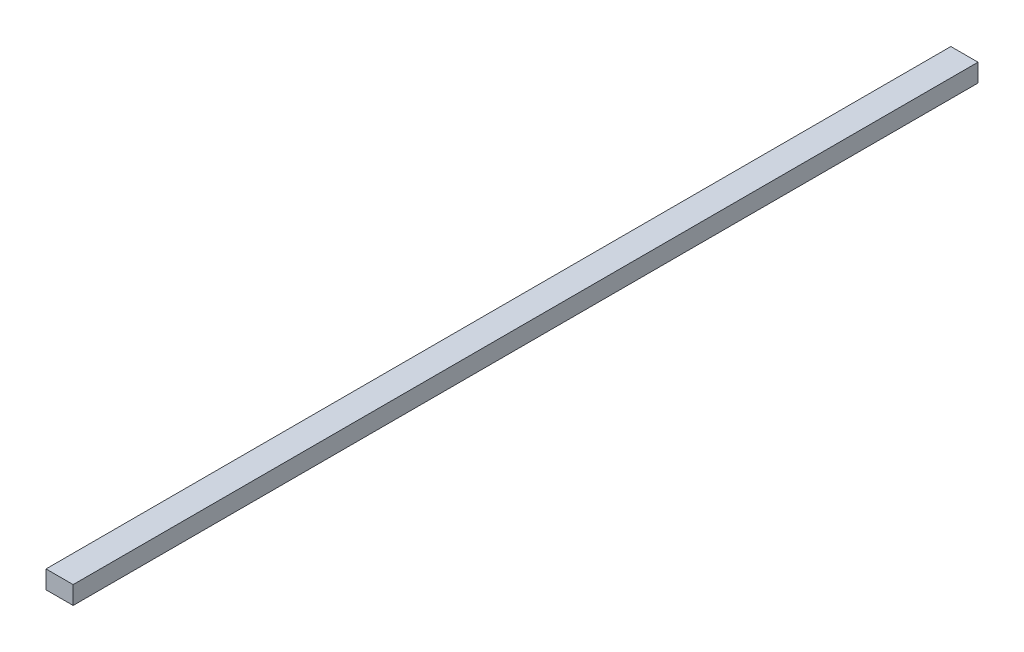
SolidWorks part; units mm, degrees
ref_plane "Front Plane" through (0, 0, 0) normal (0, 0, 1) x (1, 0, 0)
ref_plane "Top Plane" through (0, 0, 0) normal (0, 1, 0) x (1, 0, 0)
ref_plane "Right Plane" through (0, 0, 0) normal (1, 0, 0) x (0, 0, -1)
sketch "Sketch1" plane through (0, 0, 0) normal (0, 1, 0) x (1, 0, 0)
  line L1 (0, 0) -> (12, 0)
  line L2 (0, 0) -> (0, 400)
  line L3 (0, 400) -> (12, 400)
  line L4 (12, 0) -> (12, 400)
  dimension "D1" = 12
  dimension "D2" = 400
extrude "Boss-Extrude1" add sketch "Sketch1" along normal blind 8 contours L1 L4 L3 L2
